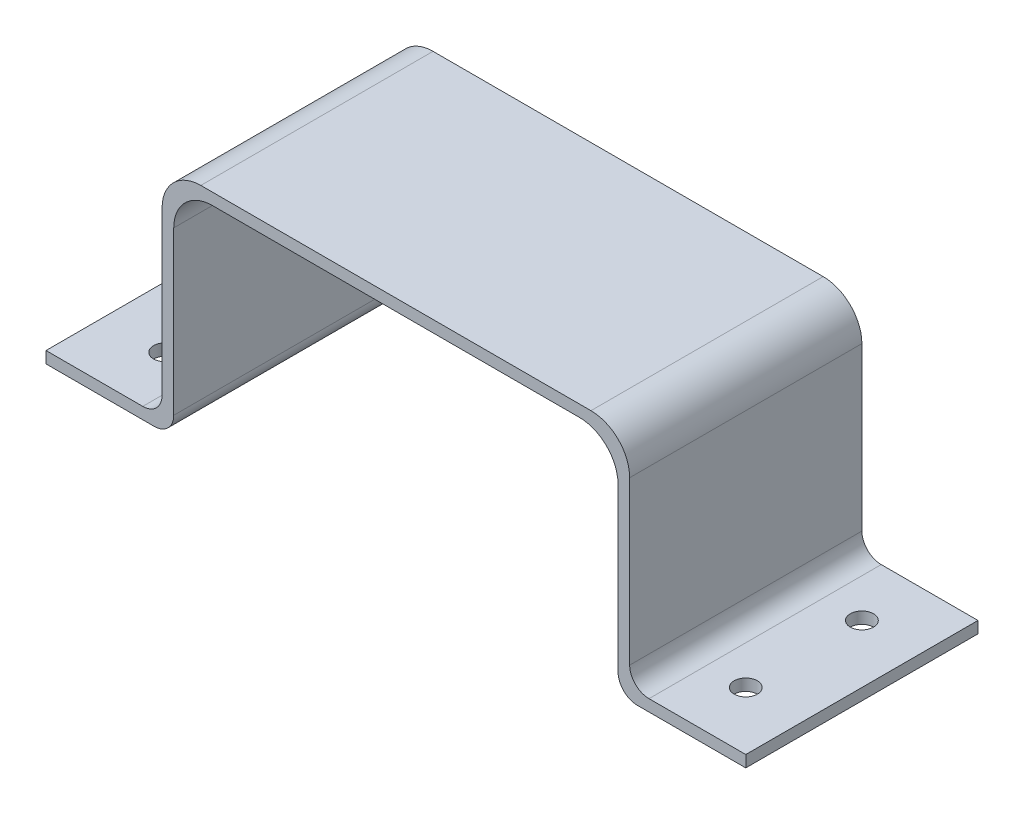
SolidWorks part; units mm, degrees
ref_plane "Front Plane" through (0, 0, 0) normal (0, 0, 1) x (1, 0, 0)
ref_plane "Top Plane" through (0, 0, 0) normal (0, 1, 0) x (1, 0, 0)
ref_plane "Right Plane" through (0, 0, 0) normal (1, 0, 0) x (0, 0, -1)
sketch "Sketch1" plane through (0, 0, 0) normal (0, 0, 1) x (1, 0, 0)
  line L0 (0, 0) -> (-120.8, 0)
  line L1 (-120.8, 0) -> (-120.8, -56.94)
  line L2 (0, 0) -> (0, -56.94)
  line L3 (-120.8, -56.94) -> (-150.8, -56.94)
  line L4 (0, -56.94) -> (30, -56.94)
  dimension "D1" = 56.94
  dimension "D2" = 120.8
  dimension "D3" = 30
  dimension "D4" = 30
extrude "Extrude-Thin1" add sketch "Sketch1" along normal blind 60 thin thin type one direction wall 3
sketch "Sketch2" plane through (0, -56.94, 0) normal (0, 1, 0) x (1, 0, 0)
  line L0 (30, 0) -> (30, -60) construction
  line L1 (15, -15) -> (30, 0) construction
  line L2 (0, 0) -> (30, 0) construction
  line L4 (0, -60) -> (0, 0) construction
  line L5 (30, -30) -> (27.0756, -30) construction
  line L6 (0, -30) -> (30, -30) construction
  line L7 (15, -15) -> (0, 0) construction
  circle A0 centre (15, -15) radius 3
  dimension "D1" = 6
extrude "Cut-Extrude1" cut sketch "Sketch2" against normal blind 10
pattern_linear "LPattern1" count 2 spacing 30 along (0, 0, 1) of "Cut-Extrude1"
pattern_linear "LPattern2" count 2 spacing 150 along (-1, 0, 0) of "LPattern1", "Cut-Extrude1"
fillet "Fillet1" radius 10 2 edges at (0, 0, 30) (-120.8, 0, 30)
fillet "Fillet2" radius 10 2 edges at (-117.8, -3, 30) (-3, -3, 30)
fillet "Fillet3" radius 5 2 edges at (0, -56.94, 30) (-120.8, -56.94, 30)
fillet "Fillet4" radius 5 2 edges at (-117.8, -59.94, 30) (-3, -59.94, 30)
